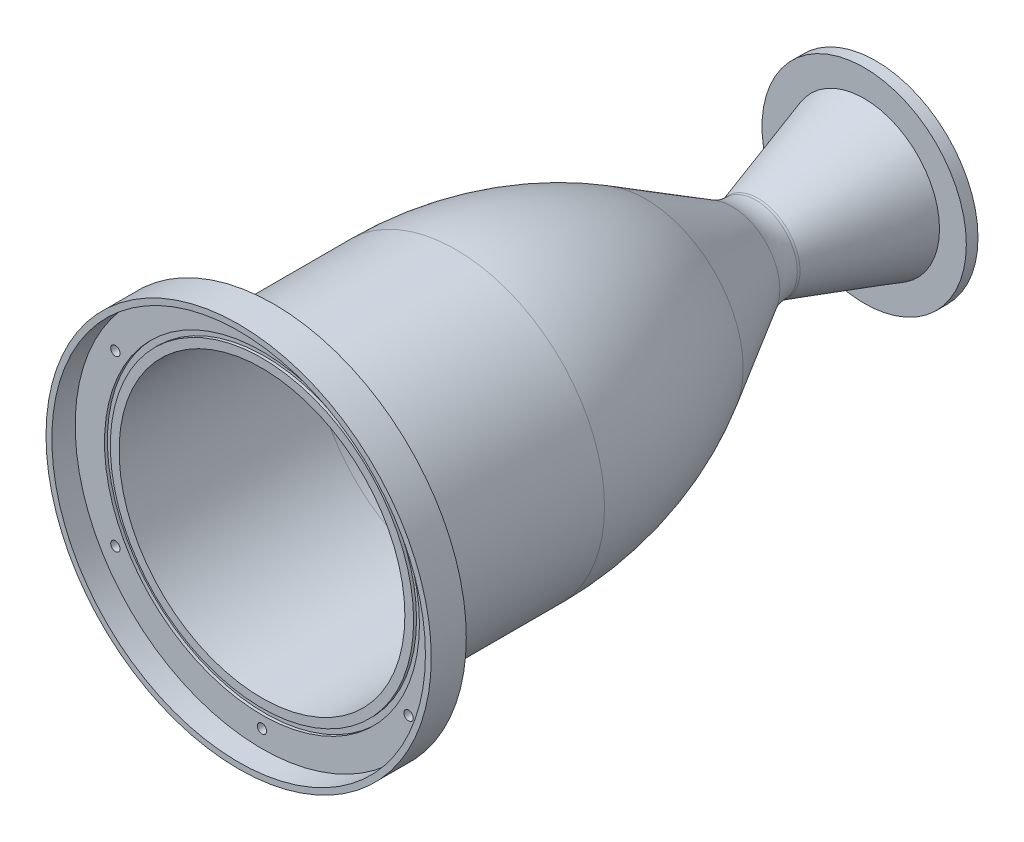
SolidWorks part; units mm, degrees
material "Copper"
ref_plane "Front Plane" through (0, 0, 0) normal (0, 0, 1) x (1, 0, 0)
ref_plane "Top Plane" through (0, 0, 0) normal (0, 1, 0) x (1, 0, 0)
ref_plane "Right Plane" through (0, 0, 0) normal (1, 0, 0) x (0, 0, -1)
ref_axis "CENTER" through (0, 0, 2.6861) along (0, 0, -1)
sketch "Sketch2" plane through (0, 0, 0) normal (1, 0, 0) x (0, 0, -1)
  line L0 (0, 24.4792) -> (33.2021, 24.4792)
  line L1 (65.1663, 15.9144) -> (80.0009, 7.3496)
  line L2 (0, 0) -> (104.6278, 0) construction
  arc A0 (65.1663, 15.9144) -> (33.2021, 24.4792) centre (33.2021, -39.4491) ccw
  arc A1 (80.0009, 7.3496) -> (84.5908, 6.1198) centre (84.5908, 15.2995) ccw
  arc A2 (84.5908, 6.1198) -> (85.3099, 6.2331) centre (84.5908, 8.4576) ccw
  spline S0 degree 2 poles (85.3099, 6.2331) (100.4469, 11.1265) (104.6278, 12.3351) knots 0 0 0 1 1 1
sketch "Sketch3" plane through (0, 0, 0) normal (1, 0, 0) x (0, 0, -1)
  line L0 (0, 24.4792) -> (33.2021, 24.4792) construction
  line L1 (65.1663, 15.9144) -> (80.0009, 7.3496) construction
  line L2 (0, 24.4792) -> (33.2021, 24.4792)
  line L3 (65.1663, 15.9144) -> (80.0009, 7.3496)
  line L9 (2, 33) -> (-4, 33)
  line L10 (84.9927, 7.1817) -> (103.1612, 12.9051)
  line L11 (0, 24.4792) -> (0, 32)
  line L12 (-57.8036, 0) -> (49942.1964, 0) construction
  line L13 (105.1612, 12.4867) -> (105.1612, 17.5)
  line L14 (105.1612, 17.5) -> (103.1612, 17.5)
  line L18 (65.6661, 16.7806) -> (80.501, 8.2157)
  line L19 (103.1612, 12.9051) -> (103.1612, 17.5)
  line L20 (33.2021, 25.4792) -> (2, 25.4792)
  line L21 (2, 25.4792) -> (2, 33)
  line L22 (85.3099, 6.2331) -> (47774.9822, 15029.3871) construction
  line L23 (0, 32) -> (-4, 32)
  line L24 (-4, 32) -> (-4, 33)
  arc A0 (65.1663, 15.9144) -> (33.2021, 24.4792) centre (33.2021, -39.4491) ccw construction
  arc A1 (80.0009, 7.3496) -> (84.5908, 6.1198) centre (84.5908, 15.2995) ccw construction
  arc A2 (84.5908, 6.1198) -> (85.3099, 6.2331) centre (84.5908, 8.4576) ccw construction
  arc A3 (65.1663, 15.9144) -> (33.2021, 24.4792) centre (33.2021, -39.4491) ccw
  arc A4 (80.0009, 7.3496) -> (84.5908, 6.1198) centre (84.5908, 15.2995) ccw
  arc A5 (84.5908, 6.1198) -> (85.3099, 6.2331) centre (84.5908, 8.4576) ccw
  arc A6 (65.6661, 16.7806) -> (33.2021, 25.4792) centre (33.2021, -39.4491) ccw
  arc A7 (84.5908, 7.1199) -> (84.9927, 7.1817) centre (84.5908, 8.4576) ccw
  arc A8 (80.501, 8.2157) -> (84.5908, 7.1199) centre (84.5908, 15.2995) ccw
  parabola Q0 (85.3099, 6.2331) -> (104.6278, 12.3351) focus (106.2201, 12.7219) apex (106.2229, 12.7229) construction
  parabola Q1 (85.3099, 6.2331) -> (105.1612, 12.4867) focus (106.2201, 12.7219) apex (106.2229, 12.7229)
  point P23 (0, 0)
  dimension "D2" = 2
  dimension "D3" = 66
  dimension "D4" = 24.9734
  dimension "D5" = 35
  dimension "D1" = 2
  dimension "D6" = 1
  dimension "D7" = 1
  dimension "D8" = 1
  dimension "D9" = 4
revolve "Main Base" add sketch "Sketch3" angle 360 about L2
sketch "Sketch4" plane through (0, 0, 0) normal (0, 0, 1) x (1, 0, 0)
  line L0 (0, 0) -> (0, 29) construction
  point P4 (0, 29)
  dimension "D1" = 29
hole_wizard "M2x0.4 Tapped Hole1" positions "Sketch5" profile "Sketch6" tap size "M2x0.4" standard "ANSI Metric" end condition through all
sketch "Sketch5" plane through (0, 0, 0) normal (0, 0, 1) x (1, 0, 0)
  point P0 (0, 29)
sketch "Sketch6" plane through (0, 29, 0) normal (1, 0, 0) x (0, -1, 0)
  line L0 (0, 0) -> (0, 105.1612)
  line L1 (0, 105.1612) -> (0.8, 105.1612)
  line L2 (0.8, 105.1612) -> (0.8, 0)
  line L5 (0.8, 0) -> (0, 0)
  line L11 (0, -6.35) -> (0, 107.95) construction
  dimension "Thru Tap Drill Dia." = 1.6
  dimension "Thru Tap Drill Depth" = 105.1612
cosmetic thread "Cosmetic Thread1" parameters "D2"=2
pattern_circular "CirPattern1" count 6 over 360 about axis through (0, 0, 0) along (0, 0, 1) of "M2x0.4 Tapped Hole1"
cosmetic thread "Cosmetic Thread2" parameters "D2"=2
cosmetic thread "Cosmetic Thread3" parameters "D2"=2
cosmetic thread "Cosmetic Thread4" parameters "D2"=2
cosmetic thread "Cosmetic Thread5" parameters "D2"=2
cosmetic thread "Cosmetic Thread6" parameters "D2"=2
cosmetic thread "Cosmetic Thread7" parameters "D2"=2
cosmetic thread "Cosmetic Thread8" parameters "D2"=2
cosmetic thread "Cosmetic Thread9" parameters "D2"=2
cosmetic thread "Cosmetic Thread10" parameters "D2"=2
cosmetic thread "Cosmetic Thread11" parameters "D2"=2
sketch "Sketch7" plane through (0, 0, 0) normal (1, 0, 0) x (0, 0, -1)
  line L0 (0, 33) -> (0, -33) construction
  line L1 (0, 26.9792) -> (0.5, 26.9792)
  line L2 (0, 26.9792) -> (0, 25.9792)
  line L3 (0, 25.9792) -> (0.5, 25.9792)
  line L4 (0.5, 26.9792) -> (0.5, 25.9792)
  line L5 (33.2021, 24.4792) -> (0, 24.4792) construction
  dimension "D1" = 0.5
  dimension "D2" = 1
  dimension "D3" = 1.5
revolve "Face O-Ring" cut sketch "Sketch7" angle 360 about axis through (0, 0, 2.6861) along (0, 0, -1)
